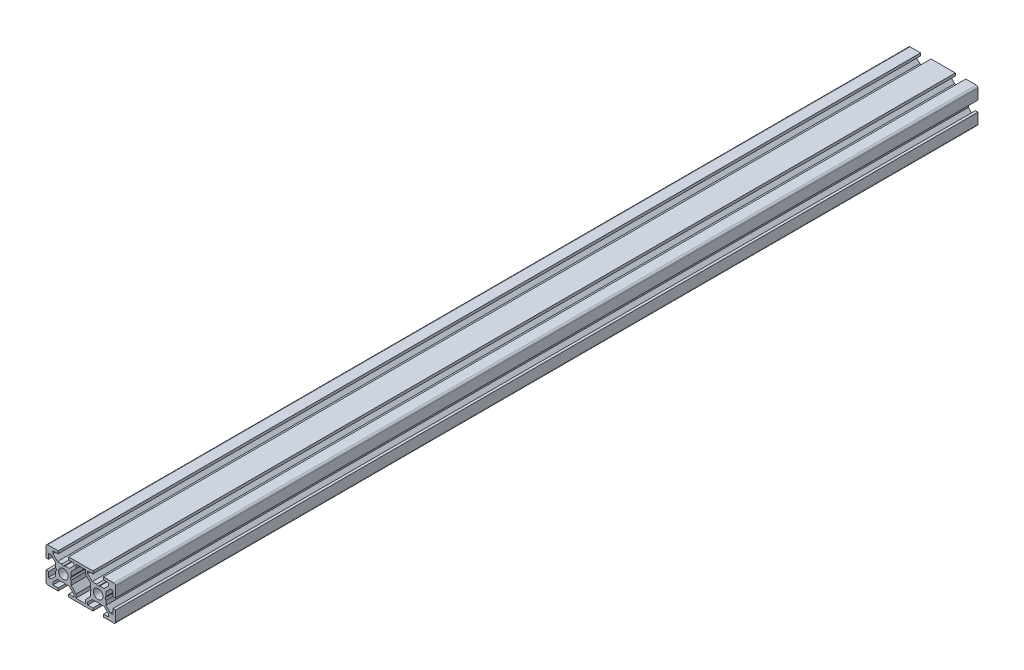
SolidWorks part; units mm, degrees
ref_plane "Front Plane" through (0, 0, 0) normal (0, 0, 1) x (1, 0, 0)
ref_plane "Top Plane" through (0, 0, 0) normal (0, 1, 0) x (1, 0, 0)
ref_plane "Right Plane" through (0, 0, 0) normal (1, 0, 0) x (0, 0, -1)
sketch "Sketch1" plane through (0, 0, 0) normal (0, 0, 1) x (1, 0, 0)
  line L0 (-707.1068, -707.1068) -> (34648.2323, 34648.2323) construction
  line L1 (-3.0018, 10) -> (-10, 10)
  line L2 (0.9376, 4.4579) -> (-0.0011, 3.9339)
  line L3 (3.4252, 4.4579) -> (0.9376, 4.4579)
  line L4 (6.0128, 7.0454) -> (3.4252, 4.4579)
  line L5 (0, -1000) -> (0, 49000) construction
  line L6 (-1000, 0) -> (49000, 0) construction
  line L7 (6.0128, 8.5) -> (6.0128, 7.0454)
  line L8 (3.0018, 8.5) -> (6.0128, 8.5)
  line L9 (3.0018, 10) -> (16.9982, 10)
  line L10 (3.0018, 8.5) -> (3.0018, 10)
  line L11 (-707.1068, 707.1068) -> (34648.2323, -34648.2323) construction
  line L12 (-7.0458, 6.0144) -> (-4.4582, 3.4268)
  line L13 (-8.5008, 6.0144) -> (-7.0458, 6.0144)
  line L14 (-8.5008, 3.0018) -> (-8.5008, 6.0144)
  line L15 (0, -0.0423) -> (0.0002, 2.0704) construction
  line L16 (-10, 3.0018) -> (-10, 10)
  line L17 (-8.5008, 3.0018) -> (-10, 3.0018)
  line L18 (7.2087, -6.4198) -> (7.2087, -8.5)
  line L19 (7.2087, -8.5) -> (12.7913, -8.5)
  line L20 (7.2087, 6.1776) -> (7.2087, 8.5)
  line L21 (7.2087, 8.5) -> (12.7913, 8.5)
  line L22 (7.2087, 6.1776) -> (4.4583, 3.4262)
  line L23 (-3.0018, 8.5) -> (-3.0018, 10)
  line L24 (-3.0018, 8.5) -> (-6.0148, 8.5)
  line L25 (-6.0148, 8.5) -> (-6.0148, 7.0458)
  line L26 (-6.0148, 7.0458) -> (-3.4272, 4.4582)
  line L27 (-3.4272, 4.4582) -> (-0.9396, 4.4582)
  line L28 (-0.9396, 4.4582) -> (-0.0011, 3.9339)
  line L29 (-4.4582, 3.4268) -> (-4.4582, 0.9396)
  line L30 (-4.4582, 0.9396) -> (-3.9347, 0)
  line L31 (4.4575, 0.9396) -> (3.9347, 0)
  line L32 (4.4583, 3.4262) -> (4.4575, 0.9396)
  line L33 (10, -990) -> (10, 49010) construction
  line L34 (19.0624, -4.4579) -> (20.0011, -3.9339)
  line L35 (16.5748, -4.4579) -> (19.0624, -4.4579)
  line L36 (13.9872, -7.0454) -> (16.5748, -4.4579)
  line L37 (-0.9396, -4.4582) -> (-0.0011, -3.9339)
  line L38 (13.9872, -8.5) -> (13.9872, -7.0454)
  line L39 (16.9982, -8.5) -> (13.9872, -8.5)
  line L40 (16.9982, -8.5) -> (16.9982, -10)
  line L41 (24.4575, -0.9396) -> (23.9347, 0)
  line L42 (24.4582, -3.4268) -> (24.4575, -0.9396)
  line L43 (27.0458, -6.0144) -> (24.4582, -3.4268)
  line L44 (28.5008, -6.0144) -> (27.0458, -6.0144)
  line L45 (-3.4272, -4.4582) -> (-0.9396, -4.4582)
  line L46 (-6.0148, -7.0458) -> (-3.4272, -4.4582)
  line L47 (-6.0148, -8.5) -> (-6.0148, -7.0458)
  line L48 (-3.0018, -8.5) -> (-6.0148, -8.5)
  line L49 (-3.0018, -10) -> (-10, -10)
  line L50 (-3.0018, -8.5) -> (-3.0018, -10)
  line L51 (4.4588, -0.9386) -> (3.9347, 0)
  line L52 (4.4583, -3.4262) -> (4.4588, -0.9386)
  line L53 (7.2087, -6.4198) -> (4.4583, -3.4262)
  line L54 (28.5008, -3.0018) -> (28.5008, -6.0144)
  line L55 (30, -3.0018) -> (30, -10)
  line L56 (28.5008, -3.0018) -> (30, -3.0018)
  line L57 (12.7913, -6.4198) -> (15.5417, -3.4262)
  line L58 (-8.5008, -3.0018) -> (-10, -3.0018)
  line L59 (-10, -3.0018) -> (-10, -10)
  line L60 (-8.5008, -3.0018) -> (-8.5008, -6.0144)
  line L61 (-8.5008, -6.0144) -> (-7.0458, -6.0144)
  line L62 (-7.0458, -6.0144) -> (-4.4582, -3.4268)
  line L63 (-4.4582, -3.4268) -> (-4.4575, -0.9396)
  line L64 (-4.4575, -0.9396) -> (-3.9347, 0)
  line L65 (3.0018, -8.5) -> (3.0018, -10)
  line L66 (3.0018, -10) -> (16.9982, -10)
  line L67 (3.0018, -8.5) -> (6.0128, -8.5)
  line L68 (6.0128, -8.5) -> (6.0128, -7.0454)
  line L69 (6.0128, -7.0454) -> (3.4252, -4.4579)
  line L70 (3.4252, -4.4579) -> (0.9376, -4.4579)
  line L71 (0.9376, -4.4579) -> (-0.0011, -3.9339)
  line L72 (15.5417, -3.4262) -> (15.5412, -0.9386)
  line L73 (15.5412, -0.9386) -> (16.0653, 0)
  line L74 (23.0018, -8.5) -> (23.0018, -10)
  line L75 (23.0018, -10) -> (30, -10)
  line L76 (23.0018, -8.5) -> (26.0148, -8.5)
  line L77 (26.0148, -8.5) -> (26.0148, -7.0458)
  line L78 (26.0148, -7.0458) -> (23.4272, -4.4582)
  line L79 (23.4272, -4.4582) -> (20.9396, -4.4582)
  line L80 (20.9396, -4.4582) -> (20.0011, -3.9339)
  line L81 (15.5417, 3.4262) -> (15.5425, 0.9396)
  line L82 (15.5425, 0.9396) -> (16.0653, 0)
  line L83 (24.4582, 0.9396) -> (23.9347, 0)
  line L84 (24.4582, 3.4268) -> (24.4582, 0.9396)
  line L85 (20.9396, 4.4582) -> (20.0011, 3.9339)
  line L86 (23.4272, 4.4582) -> (20.9396, 4.4582)
  line L87 (26.0148, 7.0458) -> (23.4272, 4.4582)
  line L88 (26.0148, 8.5) -> (26.0148, 7.0458)
  line L89 (23.0018, 8.5) -> (26.0148, 8.5)
  line L90 (23.0018, 8.5) -> (23.0018, 10)
  line L91 (12.7913, 6.1776) -> (15.5417, 3.4262)
  line L92 (12.7913, 6.1776) -> (12.7913, 8.5)
  line L93 (12.7913, -6.4198) -> (12.7913, -8.5)
  line L94 (28.5008, 3.0018) -> (30, 3.0018)
  line L95 (30, 3.0018) -> (30, 10)
  line L96 (28.5008, 3.0018) -> (28.5008, 6.0144)
  line L97 (28.5008, 6.0144) -> (27.0458, 6.0144)
  line L98 (27.0458, 6.0144) -> (24.4582, 3.4268)
  line L99 (16.9982, 8.5) -> (16.9982, 10)
  line L100 (16.9982, 8.5) -> (13.9872, 8.5)
  line L101 (13.9872, 8.5) -> (13.9872, 7.0454)
  line L102 (13.9872, 7.0454) -> (16.5748, 4.4579)
  line L103 (16.5748, 4.4579) -> (19.0624, 4.4579)
  line L104 (19.0624, 4.4579) -> (20.0011, 3.9339)
  line L105 (23.0018, 10) -> (30, 10)
  circle A0 centre (0, 0) radius 2.75
  circle A1 centre (20, 0) radius 2.75
  point P76 (10, -10)
  point P79 (10, -10)
  point P88 (10, -3.0018)
  point P111 (10, 8.5)
  point P112 (10, -8.5)
  point P114 (10, 3.0018)
  point P120 (10, 10)
  point P121 (10, 10)
extrude "Boss-Extrude1" add sketch "Sketch1" along normal blind 496
fillet "Fillet2" radius 1 1 edges at (-10, -10, 248)
fillet "Fillet4" radius 1 1 edges at (-10, 10, 248)
fillet "Fillet5" radius 1 1 edges at (30, 10, 248)
fillet "Fillet6" radius 1 1 edges at (30, -10, 248)
